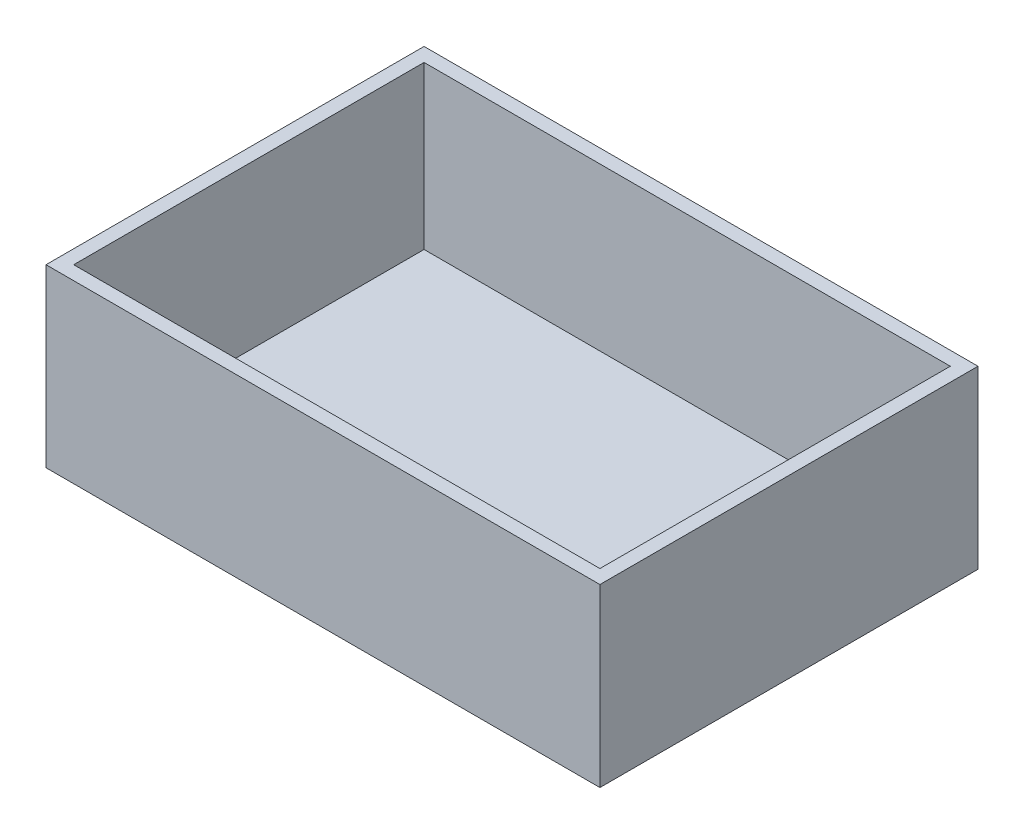
SolidWorks part; units mm, degrees
ref_plane "Plano frontal" through (0, 0, 0) normal (0, 0, 1) x (1, 0, 0)
ref_plane "Plano superior" through (0, 0, 0) normal (0, 1, 0) x (1, 0, 0)
ref_plane "Plano direito" through (0, 0, 0) normal (1, 0, 0) x (0, 0, -1)
sketch "Esboço2" plane through (0, 0, 0) normal (0, 1, 0) x (1, 0, 0)
  line L1 (0, 0) -> (50.4, 0)
  line L2 (0, 0) -> (0, -34.4)
  line L3 (0, -34.4) -> (50.4, -34.4)
  line L4 (50.4, 0) -> (50.4, -34.4)
  dimension "D1" = 50.4
  dimension "D2" = 34.4
extrude "Ressalto-extrusão1" add sketch "Esboço2" along normal blind 16
shell "Casca1" thickness 1.26
